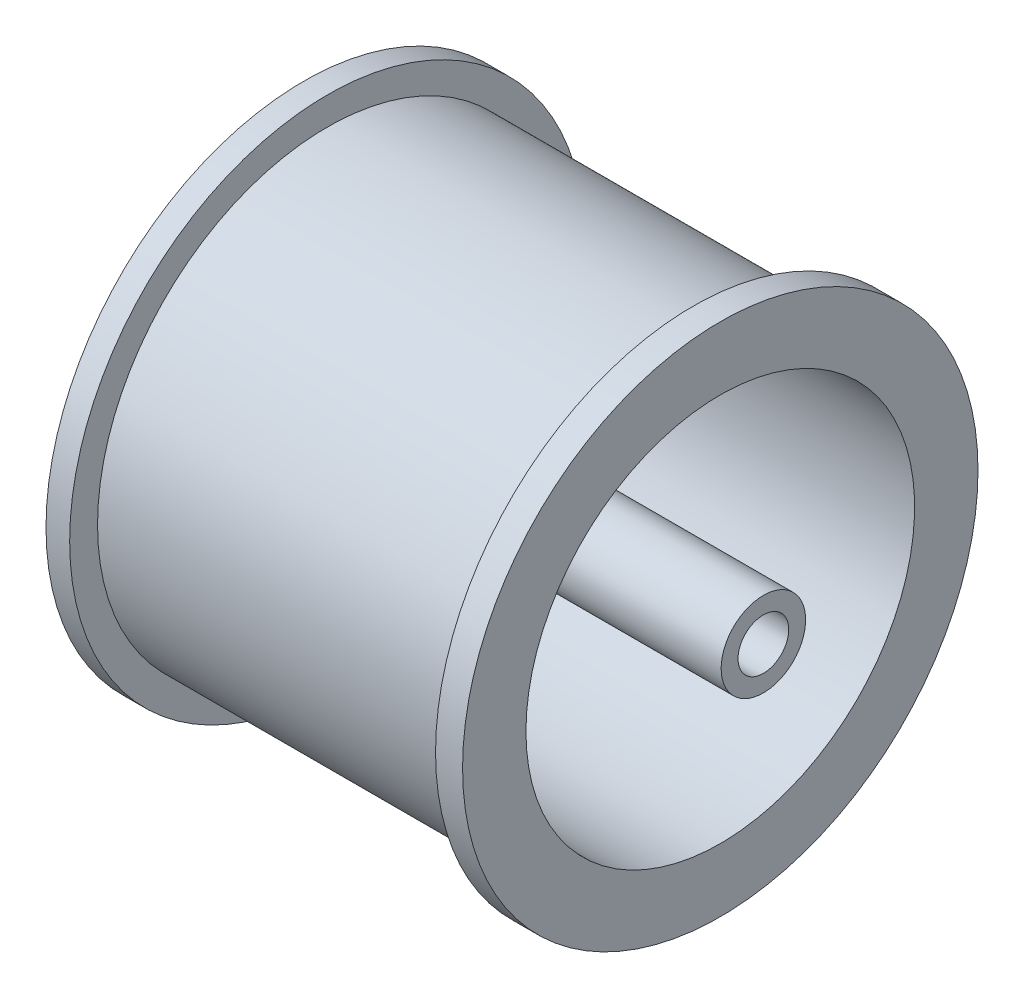
SolidWorks part; units mm, degrees
ref_plane "Front Plane" through (0, 0, 0) normal (0, 0, 1) x (1, 0, 0)
ref_plane "Top Plane" through (0, 0, 0) normal (0, 1, 0) x (1, 0, 0)
ref_plane "Right Plane" through (0, 0, 0) normal (1, 0, 0) x (0, 0, -1)
sketch "Sketch1" plane through (0, 0, 0) normal (0, 0, 1) x (1, 0, 0)
  line L0 (0, 0) -> (15.4859, 0) construction
  line L1 (0, 15.25) -> (0, 11.5)
  line L2 (0, 11.5) -> (3.6, 11.5)
  line L3 (3.6, 11.5) -> (3.6, 10)
  line L4 (3.6, 10) -> (6.6, 10)
  line L5 (6.6, 10) -> (6.6, 11.5)
  line L6 (6.6, 11.5) -> (24.65, 11.5)
  line L7 (24.65, 11.5) -> (24.65, 15.25)
  line L8 (24.65, 15.25) -> (23.05, 15.25)
  line L9 (23.05, 15.25) -> (23.05, 13.6)
  line L10 (23.05, 13.6) -> (1.4, 13.6)
  line L11 (1.4, 13.6) -> (1.4, 15.25)
  line L12 (1.4, 15.25) -> (0, 15.25)
  point P5 (5.1, 10)
  point P16 (1.8, 11.5)
  dimension "D1" = 10
  dimension "D2" = 11.5
  dimension "D3" = 13.6
  dimension "D4" = 15.25
  dimension "D5" = 3
  dimension "D6" = 3.6
  dimension "D7" = 24.65
  dimension "D8" = 1.6
  dimension "D9" = 1.4
revolve "Revolve1" add sketch "Sketch1" angle 360 about L0
sketch "Sketch3" plane through (0, 0, 0) normal (0, 0, 1) x (1, 0, 0)
  line L0 (0, 0) -> (38.2444, 0) construction
  line L1 (0, 11.5) -> (0, -11.5) construction
  line L2 (1.5, 0) -> (27.2, 0)
  line L3 (27.2, 0) -> (27.2, 2.5)
  line L4 (27.2, 2.5) -> (5.1719, 2.5)
  line L5 (5.1719, 2.5) -> (1.5, 4.62)
  line L6 (1.5, 4.62) -> (1.5, 0)
  dimension "D1" = 25.7
  dimension "D2" = 2.5
  dimension "D3" = 1.5
  dimension "D4" = 4.62
  dimension "D5" = 60
revolve "Revolve2" add sketch "Sketch3" angle 360 about L0
sketch "Sketch4" plane through (27.2, 0, 0) normal (1, 0, 0) x (0, 0, -1)
  circle A0 centre (0, 0) radius 1.5
extrude "Cut-Extrude1" cut sketch "Sketch4" against normal blind 15
sketch "Sketch5" plane through (0, 0, 0) normal (0, 0, 1) x (1, 0, 0)
  line L0 (0, 0) -> (0, 10)
  line L1 (0, 11.5) -> (0, -11.5) construction
  line L2 (0, 10) -> (3.6, 11.5)
  line L3 (3.6, 11.5) -> (3.6, -11.5) construction
  line L4 (3.6, 9.2581) -> (1.5, 8.3831)
  line L5 (3.6, 10) -> (3.6, -10) construction
  line L6 (1.5, 8.3831) -> (1.5, 0)
  line L7 (1.5, 0) -> (0, 0)
  line L8 (3.6, 9.2581) -> (3.6, 11.5)
  line L9 (3.6, 11.5) -> (3.6, 10)
  dimension "D1" = 1.5
  dimension "D2" = 11.5
  dimension "D3" = 10
revolve "Revolve4" add sketch "Sketch5" angle 360 about L7
sketch "Sketch6" plane through (0, 0, 0) normal (-1, 0, 0) x (0, 0, 1)
  line L0 (0, 0) -> (0, 10) construction
  line L1 (2.75, 5) -> (-2.75, 5)
  line L2 (-2.75, 5) -> (-5.5361, 8.3203)
  line L3 (2.75, 5) -> (5.5361, 8.3203)
  line L4 (5, 2.75) -> (8.3203, 5.5361)
  line L5 (5, -2.75) -> (5, 2.75)
  line L6 (5, -2.75) -> (8.3203, -5.5361)
  line L7 (2.75, -5) -> (5.5361, -8.3203)
  line L8 (-2.75, -5) -> (2.75, -5)
  line L9 (-2.75, -5) -> (-5.5361, -8.3203)
  line L10 (-5, -2.75) -> (-8.3203, -5.5361)
  line L11 (-5, 2.75) -> (-5, -2.75)
  line L12 (-5, 2.75) -> (-8.3203, 5.5361)
  circle A0 centre (0, 0) radius 10 construction
  arc A1 (5.5361, 8.3203) -> (-5.5361, 8.3203) centre (0, 0) ccw
  arc A2 (8.3203, -5.5361) -> (8.3203, 5.5361) centre (0, 0) ccw
  arc A3 (-5.5361, -8.3203) -> (5.5361, -8.3203) centre (0, 0) ccw
  arc A4 (-8.3203, 5.5361) -> (-8.3203, -5.5361) centre (0, 0) ccw
  point P11 (0, 5)
  point P26 (0, 0)
  dimension "D1" = 5.5
  dimension "D2" = 130
  dimension "D3" = 5
  dimension "D4" = 4
extrude "Cut-Extrude3" cut sketch "Sketch6" against normal blind 15
sketch "Sketch7" plane through (0, 0, 0) normal (0, 0, 1) x (1, 0, 0)
  line L0 (0, 0) -> (0, 4.25)
  line L1 (0, -2.75) -> (0, 2.75) construction
  line L2 (0, 4.25) -> (3.1, 2.4602)
  line L3 (3.1, 2.4602) -> (3.1, 0)
  line L4 (3.1, 0) -> (0, 0)
  dimension "D1" = 3.1
  dimension "D2" = 4.25
  dimension "D3" = 60
revolve "Cut-Revolve1" cut sketch "Sketch7" angle 360 about L4
fillet "Fillet1" radius 2 1 edges at (3.1, 2.4602, 0)
sketch "Sketch8" plane through (3.1, 0, 0) normal (-1, 0, 0) x (0, 0, 1)
  circle A0 centre (0, 0) radius 1.3055
extrude "Boss-Extrude1" add sketch "Sketch8" along normal blind 1
